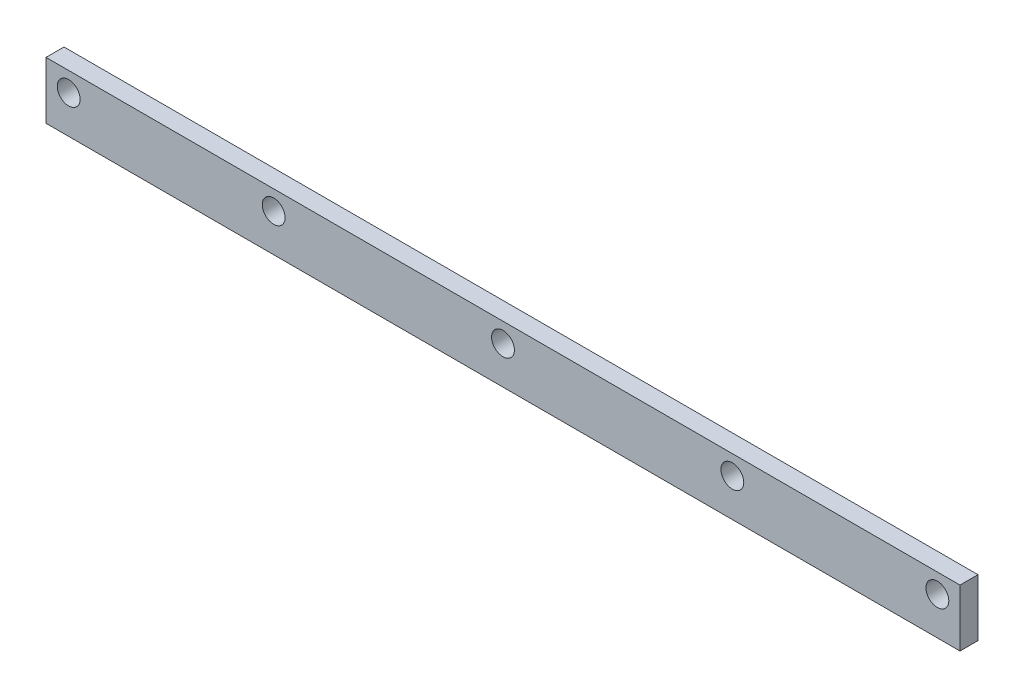
SolidWorks part; units mm, degrees
ref_plane "Front Plane" through (0, 0, 0) normal (0, 0, 1) x (1, 0, 0)
ref_plane "Top Plane" through (0, 0, 0) normal (0, 1, 0) x (1, 0, 0)
ref_plane "Right Plane" through (0, 0, 0) normal (1, 0, 0) x (0, 0, -1)
sketch "Sketch2" plane through (0, 0, 0) normal (0, 0, 1) x (1, 0, 0)
  line L0 (0, 12.7) -> (0, 0) construction
  line L1 (-101.6, 12.7) -> (101.6, 12.7)
  line L2 (-101.6, 12.7) -> (-101.6, 0)
  line L3 (-101.6, 0) -> (101.6, 0)
  line L4 (101.6, 12.7) -> (101.6, 0)
  circle A0 centre (-76.2, 30.48) radius 25.4 construction
  circle A1 centre (-25.4, 30.48) radius 25.4 construction
  circle A2 centre (25.4, 30.48) radius 25.4 construction
  circle A3 centre (76.2, 30.48) radius 25.4 construction
  circle A4 centre (-96.562, 8.3989) radius 2.54
  circle A5 centre (-50.9847, 8.3989) radius 2.54
  circle A6 centre (96.562, 8.3989) radius 2.54
  circle A7 centre (0, 8.3989) radius 2.54
  circle A8 centre (50.9847, 8.3989) radius 2.54
  dimension "D3" = 50.8
  dimension "D4" = 4
  dimension "D5" = 30.48
  dimension "D6" = 3
  dimension "D1" = 203.2
  dimension "D2" = 12.7
extrude "Boss-Extrude2" add sketch "Sketch2" along normal mid plane 4
